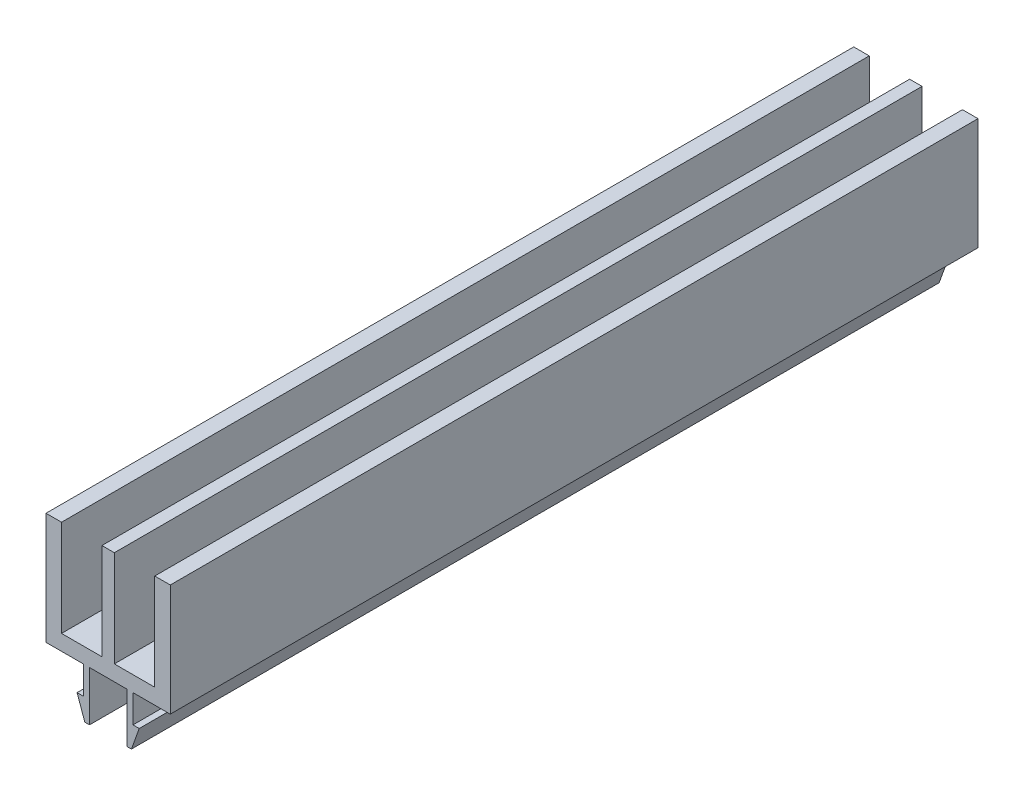
SolidWorks part; units mm, degrees
ref_plane "Plan de face" through (0, 0, 0) normal (0, 0, 1) x (1, 0, 0)
ref_plane "Plan de dessus" through (0, 0, 0) normal (0, 1, 0) x (1, 0, 0)
ref_plane "Plan de droite" through (0, 0, 0) normal (1, 0, 0) x (0, 0, -1)
ref_plane "Plan1" through (0, 0, 50) normal (0, 0, 1) x (1, 0, 0)
sketch "Esquisse1" plane through (0, 0, 50) normal (0, 0, 1) x (1, 0, 0)
  line L0 (-1, 2.5) -> (-7.5, 2.5)
  line L1 (-7.5, 2.5) -> (-7.5, 18)
  line L2 (-7.5, 18) -> (-10, 18)
  line L3 (-10, 18) -> (-10, 0)
  line L4 (-10, 0) -> (-4, 0)
  line L5 (-4, 0) -> (-4, -4.5)
  line L6 (-4, -4.5) -> (-5, -4.5)
  line L7 (-5, -4.5) -> (-3.75, -8)
  line L8 (-3.75, -8) -> (-3, -8)
  line L9 (-3, -8) -> (-3, 0)
  line L10 (-3, 0) -> (3, 0)
  line L11 (3, 0) -> (3, -8)
  line L12 (3, -8) -> (3.75, -8)
  line L13 (3.75, -8) -> (5, -4.5)
  line L14 (5, -4.5) -> (4, -4.5)
  line L15 (4, -4.5) -> (4, 0)
  line L16 (4, 0) -> (10, 0)
  line L17 (10, 0) -> (10, 18)
  line L18 (10, 18) -> (7.5, 18)
  line L19 (7.5, 18) -> (7.5, 2.5)
  line L20 (7.5, 2.5) -> (1, 2.5)
  line L21 (1, 2.5) -> (1, 18)
  line L22 (1, 18) -> (-1, 18)
  line L23 (-1, 18) -> (-1, 2.5)
extrude "Boss.-Extru.1" add sketch "Esquisse1" against normal blind 130
